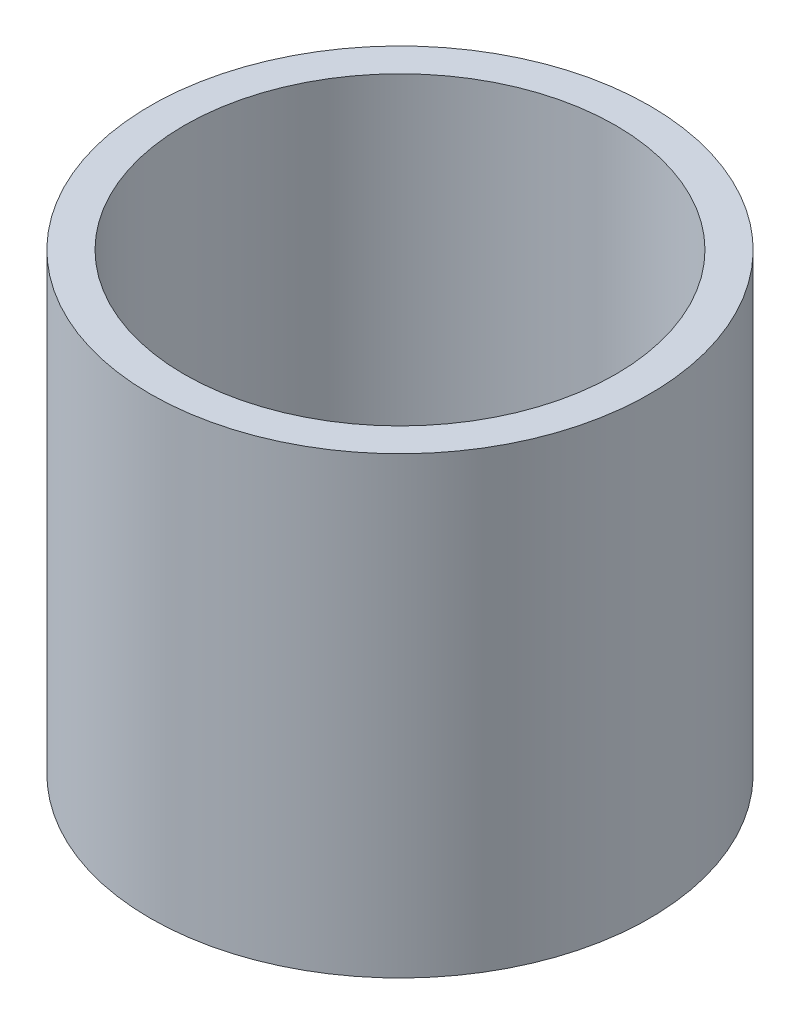
SolidWorks part; units mm, degrees
ref_plane "Ön Düzlem" through (0, 0, 0) normal (0, 0, 1) x (1, 0, 0)
ref_plane "Üst Düzlem" through (0, 0, 0) normal (0, 1, 0) x (1, 0, 0)
ref_plane "Sağ Düzlem" through (0, 0, 0) normal (1, 0, 0) x (0, 0, -1)
sketch "Sketch1" plane through (0, 0, 0) normal (0, 1, 0) x (1, 0, 0)
  circle A0 centre (0, 0) radius 22
  circle A1 centre (0, 0) radius 19
  dimension "D1" = 44
  dimension "D2" = 38
extrude "Boss-Extrude1" add sketch "Sketch1" along normal blind 40
